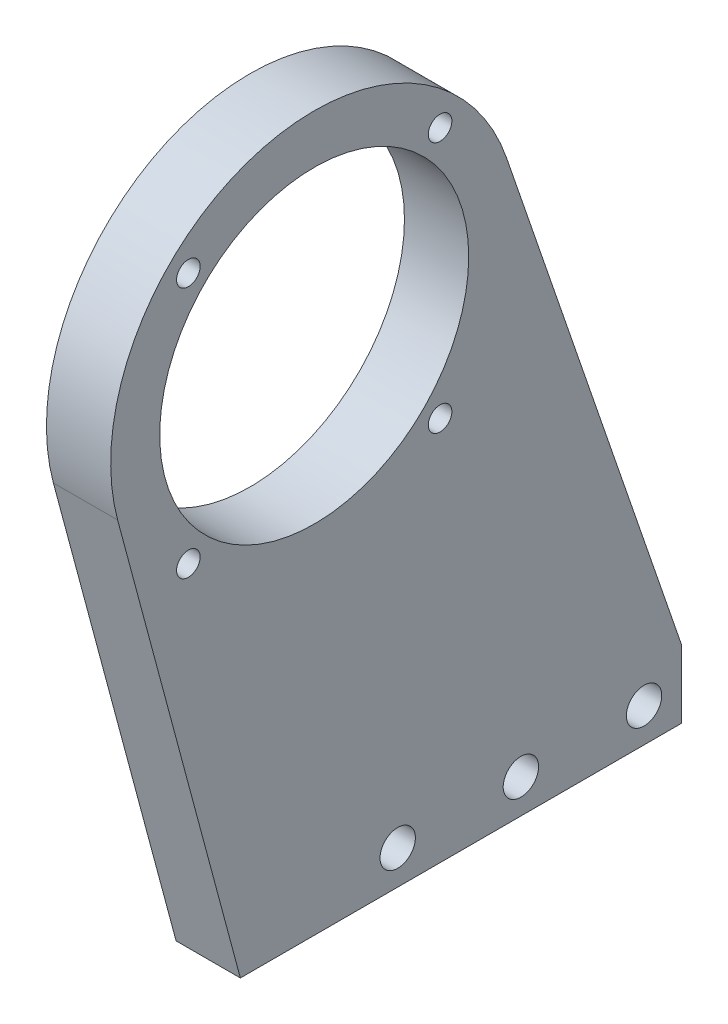
SolidWorks part; units mm, degrees
ref_plane "Front Plane" through (0, 0, 0) normal (0, 0, 1) x (1, 0, 0)
ref_plane "Top Plane" through (0, 0, 0) normal (0, 1, 0) x (1, 0, 0)
ref_plane "Right Plane" through (0, 0, 0) normal (1, 0, 0) x (0, 0, -1)
sketch "Sketch1" plane through (0, 0, 0) normal (1, 0, 0) x (0, 0, -1)
  line L0 (-36.7052, -9.8351) -> (-13.7915, -95.35)
  line L1 (-13.7915, -95.35) -> (68.5885, -95.35)
  line L2 (35.9367, 12.3514) -> (68.5885, -82.65)
  line L3 (68.5885, -82.65) -> (68.5885, -95.35)
  line L4 (68.5885, -89) -> (61.59, -89) construction
  line L5 (61.59, -89) -> (38.59, -89) construction
  line L6 (38.59, -89) -> (15.59, -89) construction
  line L7 (0, 0) -> (0, 38) construction
  line L8 (-23.5, 23.5) -> (23.5, 23.5) construction
  line L9 (-23.5, 23.5) -> (-23.5, -23.5) construction
  line L10 (-23.5, -23.5) -> (23.5, -23.5) construction
  line L11 (23.5, 23.5) -> (23.5, -23.5) construction
  line L12 (-23.5, 23.5) -> (23.5, -23.5) construction
  line L13 (-23.5, -23.5) -> (23.5, 23.5) construction
  circle A0 centre (0, 0) radius 28.85
  circle A1 centre (0, 0) radius 38
  circle A2 centre (61.59, -89) radius 3.3
  circle A3 centre (38.59, -89) radius 3.3
  circle A4 centre (15.59, -89) radius 3.3
  circle A5 centre (-23.5, 23.5) radius 2.2
  circle A6 centre (23.5, 23.5) radius 2.2
  circle A7 centre (-23.5, -23.5) radius 2.2
  circle A8 centre (23.5, -23.5) radius 2.2
  dimension "D1" = 57.7
  dimension "D2" = 76
  dimension "D7" = 23
  dimension "D8" = 6.6
  dimension "D12" = 4.4
  dimension "D3" = 82.38
  dimension "D4" = 12.7
  dimension "D5" = 120.65
  dimension "D6" = 105
  dimension "D9" = 6.35
  dimension "D10" = 15.59
  dimension "D11" = 47
extrude "Boss-Extrude1" add sketch "Sketch1" along normal blind 12.7 contours A1 A8 A7 A6 A5 A0 | A1 L0 L1 L3 L2 A4 A3 A2
other "Move Face4" face at (12.7, -47.1498, -22.3802) parameters "D1"=0.7
